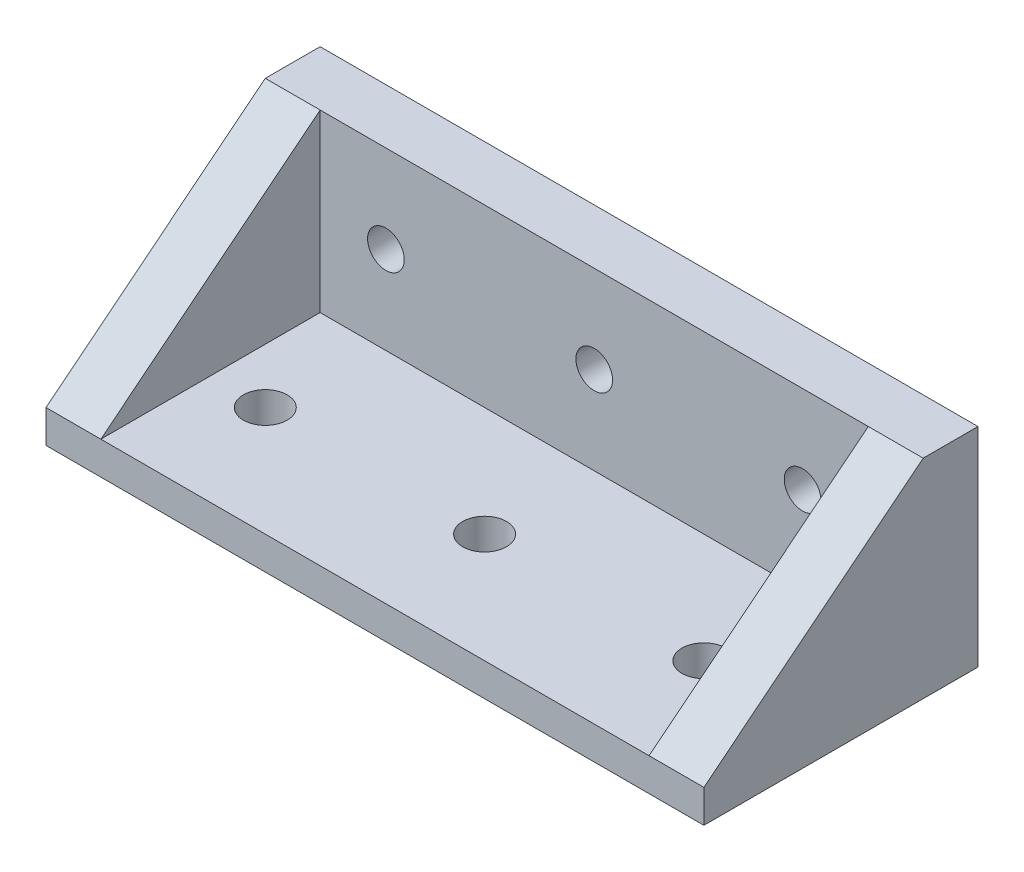
SolidWorks part; units mm, degrees
material "6061-T6 (SS)"
ref_plane "Front Plane" through (0, 0, 0) normal (0, 0, 1) x (1, 0, 0)
ref_plane "Top Plane" through (0, 0, 0) normal (0, 1, 0) x (1, 0, 0)
ref_plane "Right Plane" through (0, 0, 0) normal (1, 0, 0) x (0, 0, -1)
sketch "Sketch1" plane through (0, 0, 0) normal (0, 0, 1) x (1, 0, 0)
  line L1 (0, 0) -> (60, 0)
  line L2 (0, 0) -> (0, -19)
  line L3 (0, -19) -> (60, -19)
  line L4 (60, 0) -> (60, -19)
  dimension "D1" = 19
  dimension "D2" = 60
extrude "Boss-Extrude1" add sketch "Sketch1" along normal blind 5
sketch "Sketch2" plane through (0, 0, 5) normal (0, 0, 1) x (1, 0, 0)
  line L0 (60, -19) -> (60, 0) construction
  line L1 (0, -19) -> (60, -19)
  line L2 (0, -19) -> (0, -16)
  line L3 (0, -16) -> (60, -16)
  line L4 (60, -19) -> (60, -16)
  dimension "D1" = 3
extrude "Boss-Extrude2" add sketch "Sketch2" along normal blind 20
sketch "Sketch3" plane through (60, 0, 0) normal (1, 0, 0) x (0, 0, -1)
  line L0 (-5, 0) -> (-25, -16)
  line L1 (-25, -16) -> (-5, -16)
  line L2 (-5, -16) -> (-5, 0)
extrude "Boss-Extrude3" add sketch "Sketch3" against normal blind 5
ref_plane "Plane1" through (30, 0, 0) normal (1, 0, 0) x (0, 0, -1)
mirror "Mirror1" about plane through (30, 0, 0) normal (1, 0, 0) of "Boss-Extrude3"
sketch "Sketch4" plane through (0, 0, 5) normal (0, 0, 1) x (1, 0, 0)
  line L0 (5, -8) -> (55, -8) construction
  line L1 (5, 0) -> (5, -16) construction
  line L2 (55, 0) -> (55, -16) construction
  circle A0 centre (11, -8) radius 1.6729
  circle A1 centre (30, -8) radius 1.6729
  circle A2 centre (49, -8) radius 1.6729
  point P9 (0, 0)
  point P15 (0, 0)
  point P16 (30, -8)
  dimension "D2" = 3
extrude "Cut-Extrude1" cut sketch "Sketch4" against normal blind 5
sketch "Sketch5" plane through (0, -16, 0) normal (0, 1, 0) x (1, 0, 0)
  line L0 (5, -15) -> (55, -15) construction
  line L1 (5, -5) -> (5, -25) construction
  line L2 (55, -5) -> (55, -25) construction
  circle A0 centre (10, -15) radius 2
  circle A1 centre (30, -15) radius 2
  circle A2 centre (50, -15) radius 2
  point P8 (0, 0)
  point P13 (30, -15)
  dimension "D1" = 3
  dimension "D2" = 4
extrude "Cut-Extrude2" cut sketch "Sketch5" against normal blind 5
